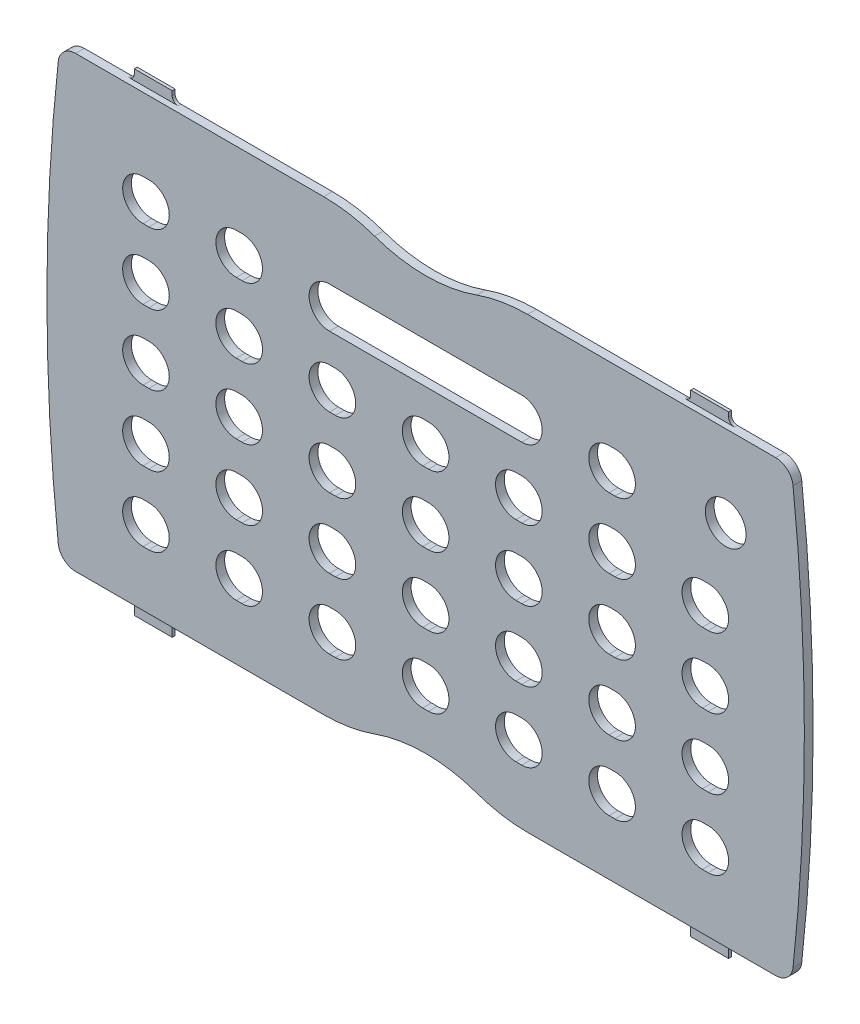
SolidWorks part; units mm, degrees
ref_plane "Front Plane" through (0, 0, 0) normal (0, 0, 1) x (1, 0, 0)
ref_plane "Top Plane" through (0, 0, 0) normal (0, 1, 0) x (1, 0, 0)
ref_plane "Right Plane" through (0, 0, 0) normal (1, 0, 0) x (0, 0, -1)
sketch "Sketch1" plane through (0, 0, 0) normal (0, 0, 1) x (1, 0, 0)
  line L0 (-125.5, -77) -> (125.5, -77)
  line L1 (-125.5, 77) -> (125.5, 77)
  line L2 (-130, 0) -> (130, 0) construction
  line L3 (0, -77) -> (0, 77) construction
  arc A0 (-125.5, 77) -> (-125.5, -77) centre (531.0278, 0) ccw
  arc A1 (125.5, 77) -> (125.5, -77) centre (-531.0278, 0) cw
  dimension "D1" = 154
  dimension "D2" = 260
  dimension "D3" = 4.5
extrude "Outside" add sketch "Sketch1" along normal blind 3
fillet "Corner" radius 6 4 edges at (125.5, -77, 1.5) (-125.5, -77, 1.5) (-125.5, 77, 1.5) (125.5, 77, 1.5)
sketch "Sketch2" plane through (0, 0, 3) normal (0, 0, 1) x (1, 0, 0)
  line L3 (-125.5, -77) -> (125.5, -77) construction
  line L4 (-112, -63) -> (-80, -63) construction
  line L5 (-112, -63) -> (-112, -39) construction
  line L6 (-112, -39) -> (-80, -39) construction
  line L7 (-80, -63) -> (-80, -39) construction
  line L8 (-112, -63) -> (-80, -39) construction
  line L9 (-112, -39) -> (-80, -63) construction
  line L10 (-97, -51) -> (-95, -51) construction
  line L11 (-97, -44) -> (-95, -44)
  line L12 (-97, -58) -> (-95, -58)
  line L13 (-80, -39) -> (-48, -39) construction
  line L14 (-80, -63) -> (-80, -39) construction
  line L15 (-80, -39) -> (-48, -63) construction
  line L16 (-80, -63) -> (-48, -39) construction
  line L17 (-80, -63) -> (-48, -63) construction
  line L18 (-48, -63) -> (-48, -39) construction
  line L19 (-48, -39) -> (-16, -39) construction
  line L20 (-48, -63) -> (-48, -39) construction
  line L21 (-48, -39) -> (-16, -63) construction
  line L22 (-48, -63) -> (-16, -39) construction
  line L23 (-48, -63) -> (-16, -63) construction
  line L24 (-16, -63) -> (-16, -39) construction
  line L25 (-16, -39) -> (16, -39) construction
  line L26 (-16, -63) -> (-16, -39) construction
  line L27 (-16, -39) -> (16, -63) construction
  line L28 (-16, -63) -> (16, -39) construction
  line L29 (-16, -63) -> (16, -63) construction
  line L30 (16, -63) -> (16, -39) construction
  line L31 (0, 0) -> (0, -123.248) construction
  line L33 (16, -39) -> (48, -39) construction
  line L34 (16, -63) -> (16, -39) construction
  line L35 (16, -39) -> (48, -63) construction
  line L36 (16, -63) -> (48, -39) construction
  line L37 (16, -63) -> (48, -63) construction
  line L38 (48, -63) -> (48, -39) construction
  line L39 (48, -39) -> (80, -39) construction
  line L40 (48, -63) -> (48, -39) construction
  line L41 (48, -39) -> (80, -63) construction
  line L42 (48, -63) -> (80, -39) construction
  line L43 (48, -63) -> (80, -63) construction
  line L44 (80, -63) -> (80, -39) construction
  line L45 (80, -39) -> (112, -39) construction
  line L46 (80, -63) -> (80, -39) construction
  line L47 (80, -39) -> (112, -63) construction
  line L48 (80, -63) -> (112, -39) construction
  line L49 (80, -63) -> (112, -63) construction
  line L50 (112, -63) -> (112, -39) construction
  line L51 (-80, -15) -> (-48, -15) construction
  line L52 (-80, -39) -> (-80, -15) construction
  line L53 (-80, -15) -> (-48, -39) construction
  line L54 (-80, -39) -> (-48, -15) construction
  line L55 (-80, -39) -> (-48, -39) construction
  line L56 (-48, -39) -> (-48, -15) construction
  line L57 (-48, -15) -> (-16, -15) construction
  line L58 (-48, -39) -> (-48, -15) construction
  line L59 (-48, -15) -> (-16, -39) construction
  line L60 (-48, -39) -> (-16, -15) construction
  line L61 (-48, -39) -> (-16, -39) construction
  line L62 (-16, -39) -> (-16, -15) construction
  line L63 (-16, -15) -> (16, -15) construction
  line L64 (-16, -39) -> (-16, -15) construction
  line L65 (-16, -15) -> (16, -39) construction
  line L66 (-16, -39) -> (16, -15) construction
  line L67 (-16, -39) -> (16, -39) construction
  line L68 (16, -39) -> (16, -15) construction
  line L69 (16, -15) -> (48, -15) construction
  line L70 (16, -39) -> (16, -15) construction
  line L71 (16, -15) -> (48, -39) construction
  line L72 (16, -39) -> (48, -15) construction
  line L73 (16, -39) -> (48, -39) construction
  line L74 (48, -39) -> (48, -15) construction
  line L75 (48, -15) -> (80, -15) construction
  line L76 (48, -39) -> (48, -15) construction
  line L77 (48, -15) -> (80, -39) construction
  line L78 (48, -39) -> (80, -15) construction
  line L79 (48, -39) -> (80, -39) construction
  line L80 (80, -39) -> (80, -15) construction
  line L81 (80, -15) -> (112, -15) construction
  line L82 (80, -39) -> (80, -15) construction
  line L83 (80, -15) -> (112, -39) construction
  line L84 (80, -39) -> (112, -15) construction
  line L85 (80, -39) -> (112, -39) construction
  line L86 (112, -39) -> (112, -15) construction
  line L87 (-80, 9) -> (-48, 9) construction
  line L88 (-80, -15) -> (-80, 9) construction
  line L89 (-80, 9) -> (-48, -15) construction
  line L90 (-80, -15) -> (-48, 9) construction
  line L91 (-80, -15) -> (-48, -15) construction
  line L92 (-48, -15) -> (-48, 9) construction
  line L93 (-48, 9) -> (-16, 9) construction
  line L94 (-48, -15) -> (-48, 9) construction
  line L95 (-48, 9) -> (-16, -15) construction
  line L96 (-48, -15) -> (-16, 9) construction
  line L97 (-48, -15) -> (-16, -15) construction
  line L98 (-16, -15) -> (-16, 9) construction
  line L99 (-16, 9) -> (16, 9) construction
  line L100 (-16, -15) -> (-16, 9) construction
  line L101 (-16, 9) -> (16, -15) construction
  line L102 (-16, -15) -> (16, 9) construction
  line L103 (-16, -15) -> (16, -15) construction
  line L104 (16, -15) -> (16, 9) construction
  line L105 (16, 9) -> (48, 9) construction
  line L106 (16, -15) -> (16, 9) construction
  line L107 (16, 9) -> (48, -15) construction
  line L108 (16, -15) -> (48, 9) construction
  line L109 (16, -15) -> (48, -15) construction
  line L110 (48, -15) -> (48, 9) construction
  line L111 (48, 9) -> (80, 9) construction
  line L112 (48, -15) -> (48, 9) construction
  line L113 (48, 9) -> (80, -15) construction
  line L114 (48, -15) -> (80, 9) construction
  line L115 (48, -15) -> (80, -15) construction
  line L116 (80, -15) -> (80, 9) construction
  line L117 (80, 9) -> (112, 9) construction
  line L118 (80, -15) -> (80, 9) construction
  line L119 (80, 9) -> (112, -15) construction
  line L120 (80, -15) -> (112, 9) construction
  line L121 (80, -15) -> (112, -15) construction
  line L122 (112, -15) -> (112, 9) construction
  line L123 (-80, 33) -> (-48, 33) construction
  line L124 (-80, 9) -> (-80, 33) construction
  line L125 (-80, 33) -> (-48, 9) construction
  line L126 (-80, 9) -> (-48, 33) construction
  line L127 (-80, 9) -> (-48, 9) construction
  line L128 (-48, 9) -> (-48, 33) construction
  line L129 (-48, 33) -> (-16, 33) construction
  line L130 (-48, 9) -> (-48, 33) construction
  line L131 (-48, 33) -> (-16, 9) construction
  line L132 (-48, 9) -> (-16, 33) construction
  line L133 (-48, 9) -> (-16, 9) construction
  line L134 (-16, 9) -> (-16, 33) construction
  line L135 (-16, 33) -> (16, 33) construction
  line L136 (-16, 9) -> (-16, 33) construction
  line L137 (-16, 33) -> (16, 9) construction
  line L138 (-16, 9) -> (16, 33) construction
  line L139 (-16, 9) -> (16, 9) construction
  line L140 (16, 9) -> (16, 33) construction
  line L141 (16, 33) -> (48, 33) construction
  line L142 (16, 9) -> (16, 33) construction
  line L143 (16, 33) -> (48, 9) construction
  line L144 (16, 9) -> (48, 33) construction
  line L145 (16, 9) -> (48, 9) construction
  line L146 (48, 9) -> (48, 33) construction
  line L147 (48, 33) -> (80, 33) construction
  line L148 (48, 9) -> (48, 33) construction
  line L149 (48, 33) -> (80, 9) construction
  line L150 (48, 9) -> (80, 33) construction
  line L151 (48, 9) -> (80, 9) construction
  line L152 (80, 9) -> (80, 33) construction
  line L153 (80, 33) -> (112, 33) construction
  line L154 (80, 9) -> (80, 33) construction
  line L155 (80, 33) -> (112, 9) construction
  line L156 (80, 9) -> (112, 33) construction
  line L157 (80, 9) -> (112, 9) construction
  line L158 (112, 9) -> (112, 33) construction
  line L159 (-80, 57) -> (-48, 57) construction
  line L160 (-80, 33) -> (-80, 57) construction
  line L161 (-80, 57) -> (-48, 33) construction
  line L162 (-80, 33) -> (-48, 57) construction
  line L163 (-80, 33) -> (-48, 33) construction
  line L164 (-48, 33) -> (-48, 57) construction
  line L165 (-48, 57) -> (-16, 57) construction
  line L166 (-48, 33) -> (-48, 57) construction
  line L167 (-48, 57) -> (-16, 33) construction
  line L168 (-48, 33) -> (-16, 57) construction
  line L169 (-48, 33) -> (-16, 33) construction
  line L170 (-16, 33) -> (-16, 57) construction
  line L171 (-16, 57) -> (16, 57) construction
  line L172 (-16, 33) -> (-16, 57) construction
  line L173 (-16, 57) -> (16, 33) construction
  line L174 (-16, 33) -> (16, 57) construction
  line L175 (-16, 33) -> (16, 33) construction
  line L176 (16, 33) -> (16, 57) construction
  line L177 (16, 57) -> (48, 57) construction
  line L178 (16, 33) -> (16, 57) construction
  line L179 (16, 57) -> (48, 33) construction
  line L180 (16, 33) -> (48, 57) construction
  line L181 (16, 33) -> (48, 33) construction
  line L182 (48, 33) -> (48, 57) construction
  line L183 (48, 57) -> (80, 57) construction
  line L184 (48, 33) -> (48, 57) construction
  line L185 (48, 57) -> (80, 33) construction
  line L186 (48, 33) -> (80, 57) construction
  line L187 (48, 33) -> (80, 33) construction
  line L188 (80, 33) -> (80, 57) construction
  line L189 (80, 57) -> (112, 57) construction
  line L190 (80, 33) -> (80, 57) construction
  line L191 (80, 57) -> (112, 33) construction
  line L192 (80, 33) -> (112, 57) construction
  line L193 (80, 33) -> (112, 33) construction
  line L194 (112, 33) -> (112, 57) construction
  line L195 (-112, -15) -> (-80, -15) construction
  line L196 (-112, -39) -> (-112, -15) construction
  line L197 (-112, -15) -> (-80, -39) construction
  line L198 (-112, -39) -> (-80, -15) construction
  line L199 (-112, -39) -> (-80, -39) construction
  line L200 (-80, -39) -> (-80, -15) construction
  line L201 (-112, 9) -> (-80, 9) construction
  line L202 (-112, -15) -> (-112, 9) construction
  line L203 (-112, 9) -> (-80, -15) construction
  line L204 (-112, -15) -> (-80, 9) construction
  line L205 (-112, -15) -> (-80, -15) construction
  line L206 (-80, -15) -> (-80, 9) construction
  line L207 (-112, 33) -> (-80, 33) construction
  line L208 (-112, 9) -> (-112, 33) construction
  line L209 (-112, 33) -> (-80, 9) construction
  line L210 (-112, 9) -> (-80, 33) construction
  line L211 (-112, 9) -> (-80, 9) construction
  line L212 (-80, 9) -> (-80, 33) construction
  line L213 (-112, 57) -> (-80, 57) construction
  line L214 (-112, 33) -> (-112, 57) construction
  line L215 (-112, 57) -> (-80, 33) construction
  line L216 (-112, 33) -> (-80, 57) construction
  line L217 (-112, 33) -> (-80, 33) construction
  line L218 (-80, 33) -> (-80, 57) construction
  arc A0 (-97, -44) -> (-97, -58) centre (-97, -51) ccw
  arc A1 (-95, -58) -> (-95, -44) centre (-95, -51) ccw
  point P0 (-96, -51)
  point P9 (-96, -51)
  dimension "D5" = 16
  dimension "D1" = 14
  dimension "D2" = 32
  dimension "D3" = 24
  dimension "D4" = 96
  dimension "D6" = 14
  dimension "D7" = 7
  dimension "D8" = 5
extrude "Cutout" cut sketch "Sketch2" against normal through all
pattern_linear "Cutouts" count 7 spacing 32 along (1, 0, 0) count 5 spacing 24 along (0, 1, 0) skipping (6, 4) of "Cutout"
sketch "Sketch4" plane through (0, 0, 3) normal (0, 0, 1) x (1, 0, 0)
  line L0 (80, 57) -> (112, 57) construction
  line L1 (112, 9) -> (112, 33) construction
  circle A0 centre (103, 49) radius 7
  dimension "D3" = 14
  dimension "D1" = 8
  dimension "D2" = 9
extrude "Top Opening" cut sketch "Sketch4" against normal through all
sketch "Sketch5" plane through (0, 0, 3) normal (0, 0, 1) x (1, 0, 0)
  line L0 (0, -77) -> (0, 77) construction
  line L1 (-125.5, -77) -> (125.5, -77) construction
  line L2 (-35, -77) -> (35, -77)
  arc A0 (-17.5, -74) -> (17.5, -74) centre (0, -123.5417) cw
  arc A1 (-17.5, -74) -> (-35, -77) centre (-35, -24.4583) cw
  arc A2 (17.5, -74) -> (35, -77) centre (35, -24.4583) ccw
  dimension "D1" = 70
  dimension "D2" = 6
extrude "Curve" cut sketch "Sketch5" against normal through all
sketch "Sketch6" plane through (0, 0, 3) normal (0, 0, 1) x (1, 0, 0)
  line L1 (-31, 38) -> (31, 38)
  line L2 (-31, 38) -> (-31, 52)
  line L3 (-31, 52) -> (31, 52)
  line L4 (31, 38) -> (31, 52)
extrude "Join" cut sketch "Sketch6" against normal through all
sketch "Sketch7" plane through (0, -77, 0) normal (0, -1, 0) x (1, 0, 0)
  line L0 (35, 0) -> (120.1407, 0) construction
  line L1 (89, 0) -> (102, 0)
  line L2 (89, 0) -> (89, 1)
  line L3 (89, 1) -> (102, 1)
  line L4 (102, 0) -> (102, 1)
  line L5 (0, 0) -> (0, 410.8012) construction
  line L6 (-120.1407, 0) -> (-35, 0) construction
  line L7 (-102, 0) -> (-89, 0)
  line L8 (-102, 0) -> (-102, 1)
  line L9 (-102, 1) -> (-89, 1)
  line L10 (-89, 0) -> (-89, 1)
  dimension "D1" = 13
  dimension "D2" = 1
  dimension "D3" = 178
extrude "Tab" add sketch "Sketch7" along normal blind 5
mirror "Tabs" about plane through (0, 0, 0) normal (0, 1, 0) of "Curve", "Tab"
fillet "Tab Corner" radius 2 8 edges at (102, -77, 0.5) (89, -77, 0.5) (-89, -77, 0.5) (-102, -77, 0.5) (-102, 77, 0.5) (-89, 77, 0.5) (89, 77, 0.5) (102, 77, 0.5)
sketch "Sketch8" plane through (0, 0, 1) normal (0, 0, 1) x (1, 0, 0)
  line L0 (-89, 82) -> (-89, 79) construction
  line L1 (-102, 82) -> (-89, 82)
  line L2 (-102, 82) -> (-102, 80.5)
  line L3 (-102, 80.5) -> (-89, 80.5)
  line L4 (-89, 82) -> (-89, 80.5)
  line L5 (102, 82) -> (102, 79) construction
  line L6 (89, 82) -> (102, 82)
  line L7 (89, 82) -> (89, 80.5)
  line L8 (89, 80.5) -> (102, 80.5)
  line L9 (102, 82) -> (102, 80.5)
  line L11 (-35, 77) -> (-87, 77) construction
  dimension "D1" = 3.5
extrude "Top Trim" cut sketch "Sketch8" against normal through all
